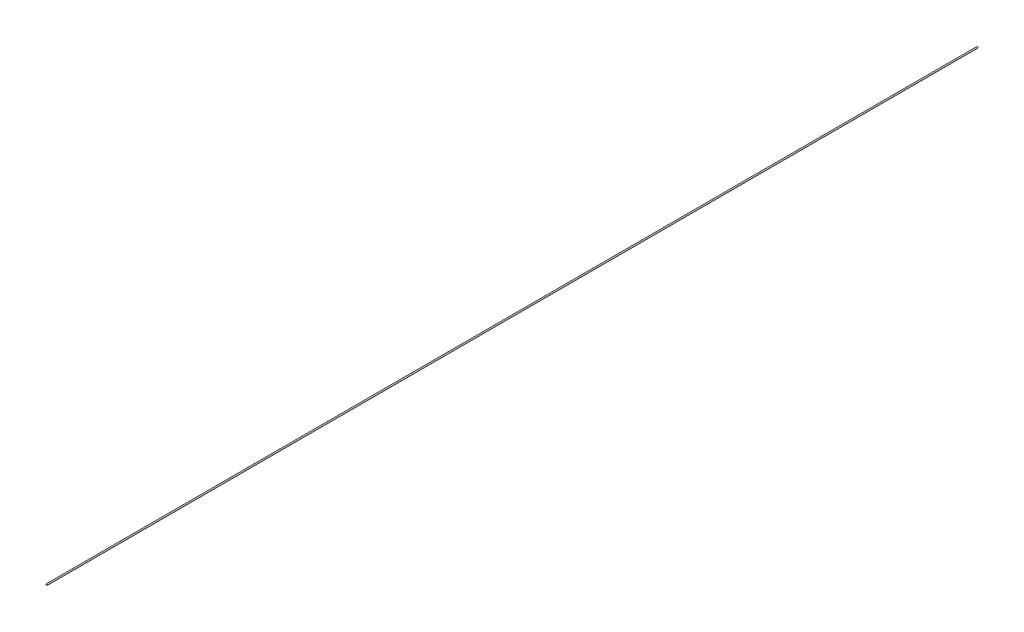
SolidWorks part; units mm, degrees
ref_plane "Front Plane" through (0, 0, 0) normal (0, 0, 1) x (1, 0, 0)
ref_plane "Top Plane" through (0, 0, 0) normal (0, 1, 0) x (1, 0, 0)
ref_plane "Right Plane" through (0, 0, 0) normal (1, 0, 0) x (0, 0, -1)
sketch "Sketch1" plane through (0, 0, 0) normal (0, 0, 1) x (1, 0, 0)
  circle A0 centre (2.7281, 0) radius 30
  dimension "D1" = 60
extrude "Boss-Extrude1" add sketch "Sketch1" along normal blind 40000
